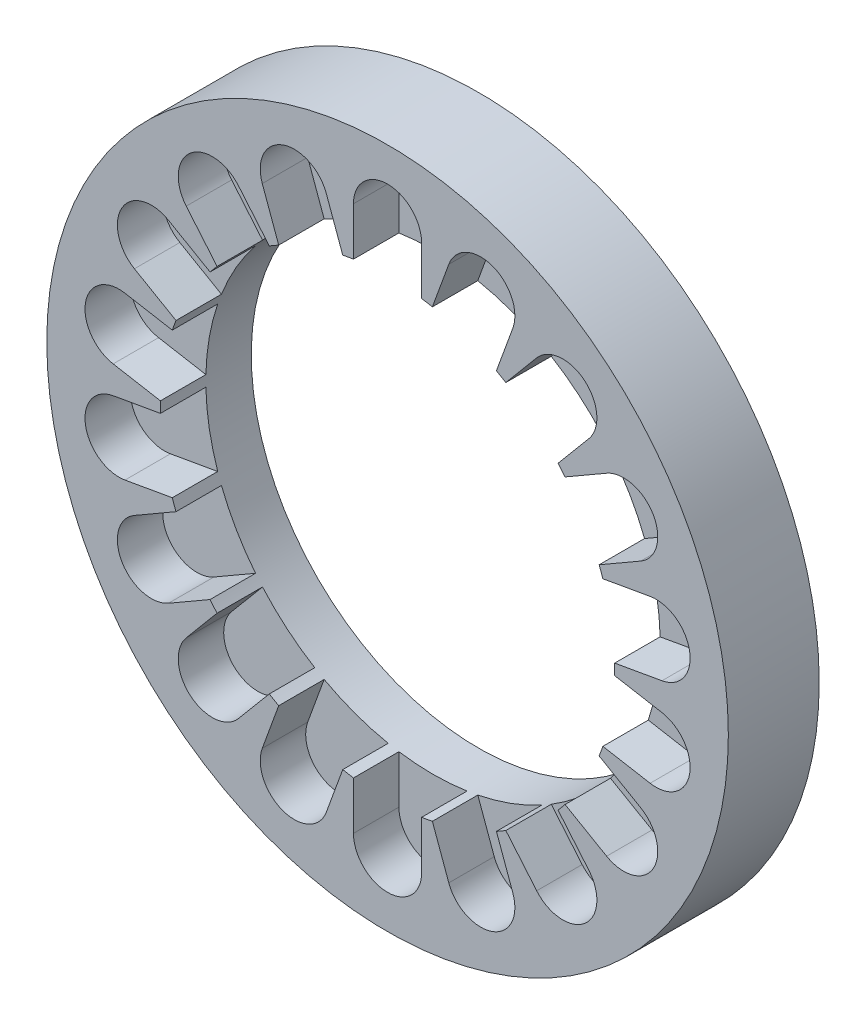
SolidWorks part; units mm, degrees
ref_plane "Front Plane" through (0, 0, 0) normal (0, 0, 1) x (1, 0, 0)
ref_plane "Top Plane" through (0, 0, 0) normal (0, 1, 0) x (1, 0, 0)
ref_plane "Right Plane" through (0, 0, 0) normal (1, 0, 0) x (0, 0, -1)
sketch "Sketch1" plane through (0, 0, 0) normal (0, 0, 1) x (1, 0, 0)
  circle A0 centre (0, 0) radius 190.5
  circle A1 centre (0, 0) radius 127
  dimension "D1" = 254
  dimension "D2" = 381
extrude "Boss-Extrude1" add sketch "Sketch1" along normal blind 50.8
sketch "Sketch2" plane through (0, 0, 50.8) normal (0, 0, 1) x (1, 0, 0)
  line L0 (0, 152.4) -> (0, -152.4) construction
  line L1 (19.05, 152.4) -> (19.05, -152.4)
  line L2 (-19.05, 152.4) -> (-19.05, -152.4)
  arc A0 (19.05, 152.4) -> (-19.05, 152.4) centre (0, 152.4) ccw
  arc A1 (-19.05, -152.4) -> (19.05, -152.4) centre (0, -152.4) ccw
  point P2 (0, 0)
  point P7 (0, 0)
  dimension "D2" = 19.05
  dimension "D1" = 304.8
extrude "Cut-Extrude1" cut sketch "Sketch2" against normal blind 25.4
pattern_circular "CirPattern1" count 10 every 20 about axis through (0, 0, 0) along (0, 0, 1) of "Cut-Extrude1"
